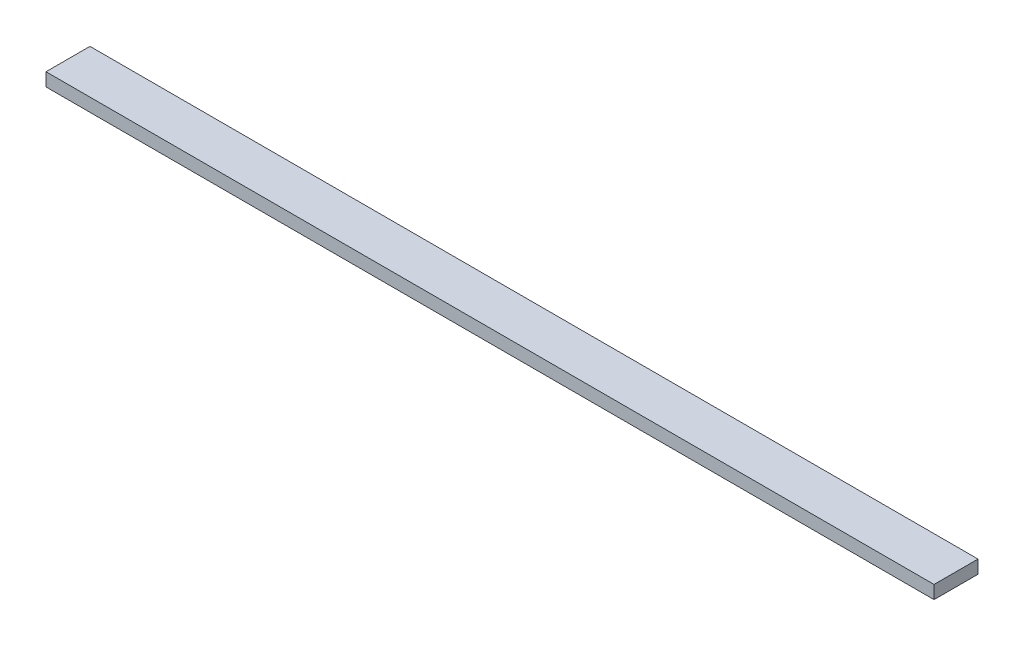
SolidWorks part; units mm, degrees
ref_plane "Front Plane" through (0, 0, 0) normal (0, 0, 1) x (1, 0, 0)
ref_plane "Top Plane" through (0, 0, 0) normal (0, 1, 0) x (1, 0, 0)
ref_plane "Right Plane" through (0, 0, 0) normal (1, 0, 0) x (0, 0, -1)
sketch "Sketch1" plane through (0, 0, 0) normal (0, 1, 0) x (1, 0, 0)
  line L1 (-101, -5) -> (101, -5)
  line L2 (-101, -5) -> (-101, 5)
  line L3 (-101, 5) -> (101, 5)
  line L4 (101, -5) -> (101, 5)
  line L5 (-101, -5) -> (101, 5) construction
  line L6 (-101, 5) -> (101, -5) construction
  point P0 (0, 0)
  dimension "D1" = 10
  dimension "D2" = 202
extrude "Boss-Extrude1" add sketch "Sketch1" along normal mid plane 3
